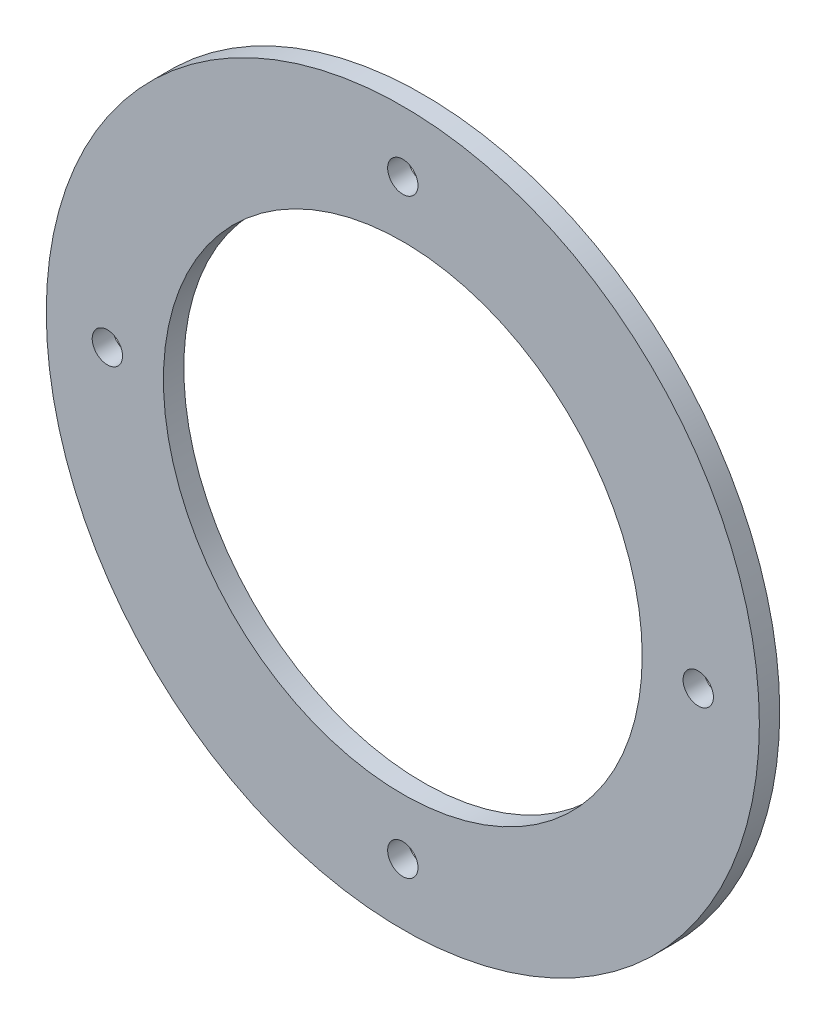
SolidWorks part; units mm, degrees
ref_plane "Front Plane" through (0, 0, 0) normal (0, 0, 1) x (1, 0, 0)
ref_plane "Top Plane" through (0, 0, 0) normal (0, 1, 0) x (1, 0, 0)
ref_plane "Right Plane" through (0, 0, 0) normal (1, 0, 0) x (0, 0, -1)
sketch "Sketch1" plane through (0, 0, 0) normal (0, 0, 1) x (1, 0, 0)
  circle A0 centre (0, 0) radius 35
  circle A1 centre (0, 0) radius 23.5
  circle A3 centre (29, 0) radius 1.49
  circle A4 centre (0, 29) radius 1.49
  circle A5 centre (-29, 0) radius 1.49
  circle A6 centre (0, -29) radius 1.49
  dimension "D1" = 70
  dimension "D2" = 47
  dimension "D3" = 2.98
  dimension "D4" = 2.98
  dimension "D5" = 2.98
  dimension "D6" = 2.98
  dimension "D7" = 29
  dimension "D8" = 29
  dimension "D9" = 29
  dimension "D10" = 29
extrude "Boss-Extrude1" add sketch "Sketch1" along normal blind 2
